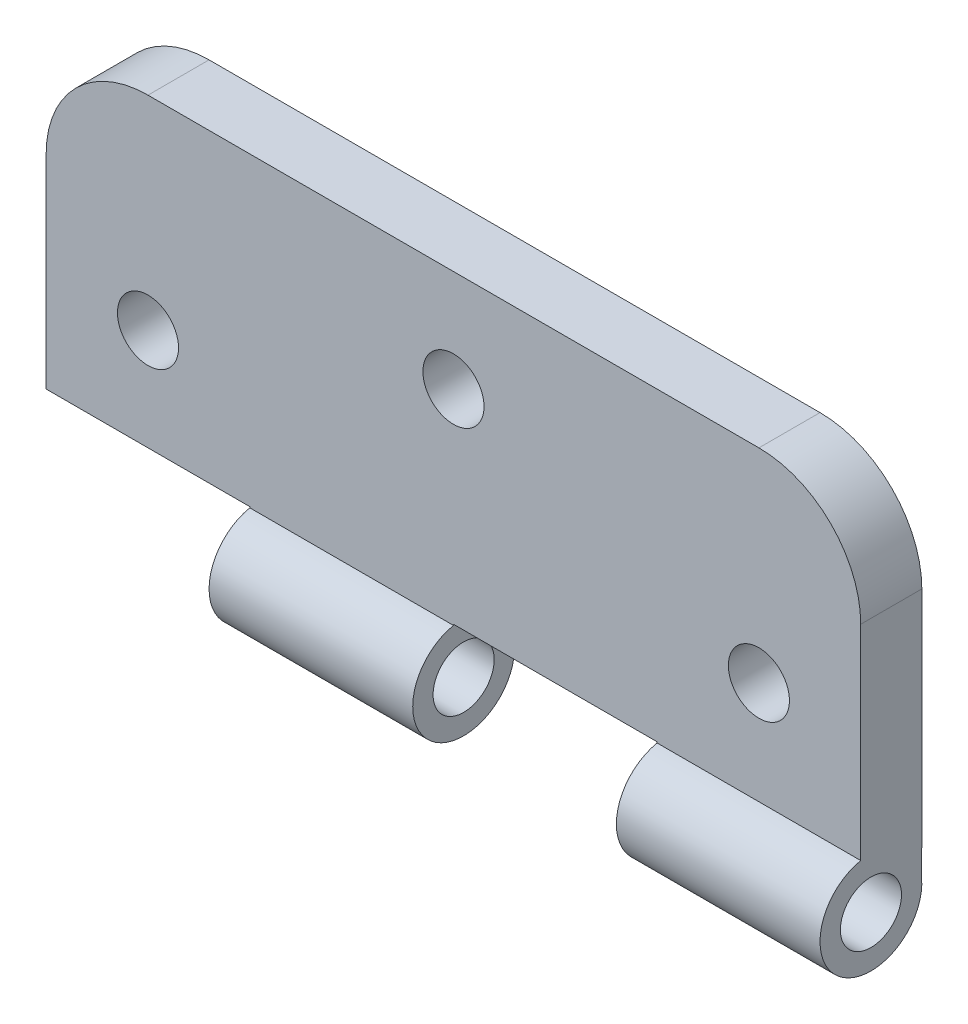
SolidWorks part; units mm, degrees
ref_plane "Plan de face" through (0, 0, 0) normal (0, 0, 1) x (1, 0, 0)
ref_plane "Plan de dessus" through (0, 0, 0) normal (0, 1, 0) x (1, 0, 0)
ref_plane "Plan de droite" through (0, 0, 0) normal (1, 0, 0) x (0, 0, -1)
sketch "Esquisse1" plane through (0, 0, 0) normal (0, 0, 1) x (1, 0, 0)
  line L0 (0, -7.5) -> (0, 7.5) construction
  line L1 (-15, 7.5) -> (15, 7.5)
  line L2 (-20, 2.5) -> (-20, -7.5)
  line L3 (-20, -7.5) -> (20, -7.5)
  line L4 (20, 2.5) -> (20, -7.5)
  line L5 (-20, 7.5) -> (20, -7.5) construction
  line L6 (-20, -7.5) -> (20, 7.5) construction
  circle A0 centre (-15, -2.5) radius 1.5
  circle A1 centre (15, -2.5) radius 1.5
  circle A2 centre (0, 2.5) radius 1.5
  arc A3 (15, 7.5) -> (20, 2.5) centre (15, 2.5) cw
  arc A4 (-15, 7.5) -> (-20, 2.5) centre (-15, 2.5) ccw
  point P0 (0, 0)
  dimension "D5" = 3
  dimension "3" = 3
  dimension "D7" = 5
  dimension "D1" = 40
  dimension "D2" = 15
  dimension "D3" = 5
  dimension "D4" = 10
  dimension "D6" = 5
extrude "Boss.-Extru.1" add sketch "Esquisse1" along normal blind 3
sketch "Esquisse2" plane through (20, 0, 0) normal (1, 0, 0) x (0, 0, -1)
  line L0 (0, -7.5) -> (0, 2.5) construction
  line L1 (-3, -7.5) -> (0, -7.5) construction
  line L2 (0, -7.5) -> (-0.0095, -9.7824)
  line L3 (-3, -7.5) -> (0, -7.5)
  line L4 (-3, -7.5) -> (-3, -7.5505)
  line L5 (-3, -7.5) -> (-2.5, -7.5)
  arc A0 (-3, -7.5505) -> (-0.0095, -9.7824) centre (-2.5, -10) ccw
  circle A1 centre (-2.5, -10) radius 1.5
  line M8 (-3, -7.5) -> (0, -7.5)
  dimension "D1" = 5
  dimension "D2" = 3
extrude "Boss.-Extru.2" add sketch "Esquisse2" against normal blind 10 contours L4 A0 L2 L3 A1 M8
pattern_linear "Répétition linéaire1" count 2 spacing 20 along (-1, 0, 0) of "Boss.-Extru.2"
